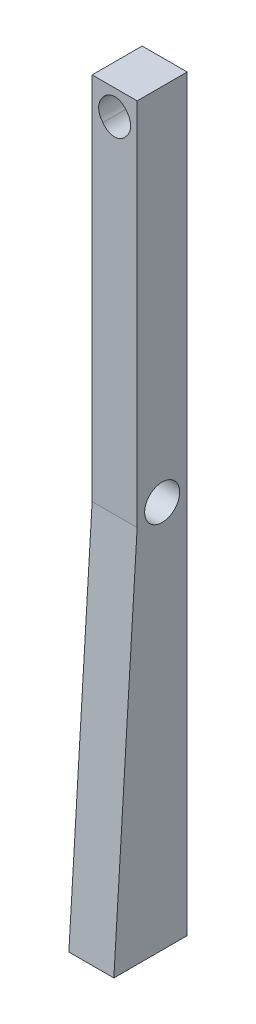
SolidWorks part; units mm, degrees
ref_plane "Plan de face" through (0, 0, 0) normal (0, 0, 1) x (1, 0, 0)
ref_plane "Plan de dessus" through (0, 0, 0) normal (0, 1, 0) x (1, 0, 0)
ref_plane "Plan de droite" through (0, 0, 0) normal (1, 0, 0) x (0, 0, -1)
sketch "Esquisse2" plane through (0, 0, 0) normal (0, 0, 1) x (1, 0, 0)
  line L0 (-14.4758, 301.5671) -> (-14.4758, 373.5671)
  line L5 (-14.4758, 373.5671) -> (-5.4758, 373.5671)
  line L18 (-5.4758, 373.5671) -> (-5.4758, 301.5671)
  line L25 (-14.4758, 301.5671) -> (-14.4758, 224.0046)
  line L26 (-14.4758, 224.0046) -> (-5.4758, 224.0046)
  line L27 (-5.4758, 301.5671) -> (-5.4758, 224.0046)
extrude "Boss.-Extru.1" add sketch "Esquisse2" along normal blind 10 contours L0 L5 L18 L27 L26 L25
sketch "Esquisse3" plane through (0, 0, 10) normal (0, 0, 1) x (1, 0, 0)
  line L0 (-5.4758, 373.5671) -> (-5.4758, 224.0046) construction
  line L1 (-14.4758, 224.0046) -> (-5.4758, 224.0046)
  line L2 (-14.4758, 224.0046) -> (-14.4758, 299.6646)
  line L3 (-14.4758, 299.6646) -> (-5.4758, 299.6646)
  line L4 (-5.4758, 224.0046) -> (-5.4758, 299.6646)
extrude "Boss.-Extru.2" add sketch "Esquisse3" along normal blind 7 contours L3 L4 L1 L2
sketch "Esquisse4" plane through (-5.4758, 0, 0) normal (1, 0, 0) x (0, 0, -1)
  line L0 (-10, 299.6646) -> (-14.6591, 224.0046)
  line L1 (-17, 224.0046) -> (0, 224.0046) construction
  line L2 (-14.6591, 224.0046) -> (-17, 224.0046)
  line L3 (-17, 224.0046) -> (-17, 299.6646)
  line L4 (-17, 299.6646) -> (-10, 299.6646)
extrude "Enlèv. mat.-Extru.1" cut sketch "Esquisse4" against normal blind 13 contours L0 L2 L3 L4
sketch "Esquisse5" plane through (0, 0, 10) normal (0, 0, 1) x (1, 0, 0)
  line L0 (-9.9758, 373.5671) -> (-9.9758, 368.5671) construction
  line L1 (-14.4758, 373.5671) -> (-5.4758, 373.5671) construction
  line L2 (-14.4758, 373.5671) -> (-14.4758, 299.6646) construction
  ellipse E0 centre (-9.9758, 368.5671) end of major axis (-9.9758, 372.0671) minor radius 3
  dimension "D1" = 4.5
  dimension "D2" = 5
extrude "Enlèv. mat.-Extru.2" cut sketch "Esquisse5" against normal blind 13 contours E0
sketch "Esquisse6" plane through (0, 0, 10) normal (0, 0, 1) x (1, 0, 0)
  circle A0 centre (-9.9758, 368.5671) radius 3.2
extrude "Enlèv. mat.-Extru.3" cut sketch "Esquisse6" against normal blind 13 contours A0
sketch "Esquisse7" plane through (-5.4758, 0, 0) normal (1, 0, 0) x (0, 0, -1)
  line L0 (-5, 373.5671) -> (-5, 301.5671) construction
  line L1 (-10, 373.5671) -> (0, 373.5671) construction
  circle A0 centre (-5, 301.5671) radius 3.5
extrude "Enlèv. mat.-Extru.4" cut sketch "Esquisse7" against normal blind 13 contours A0
